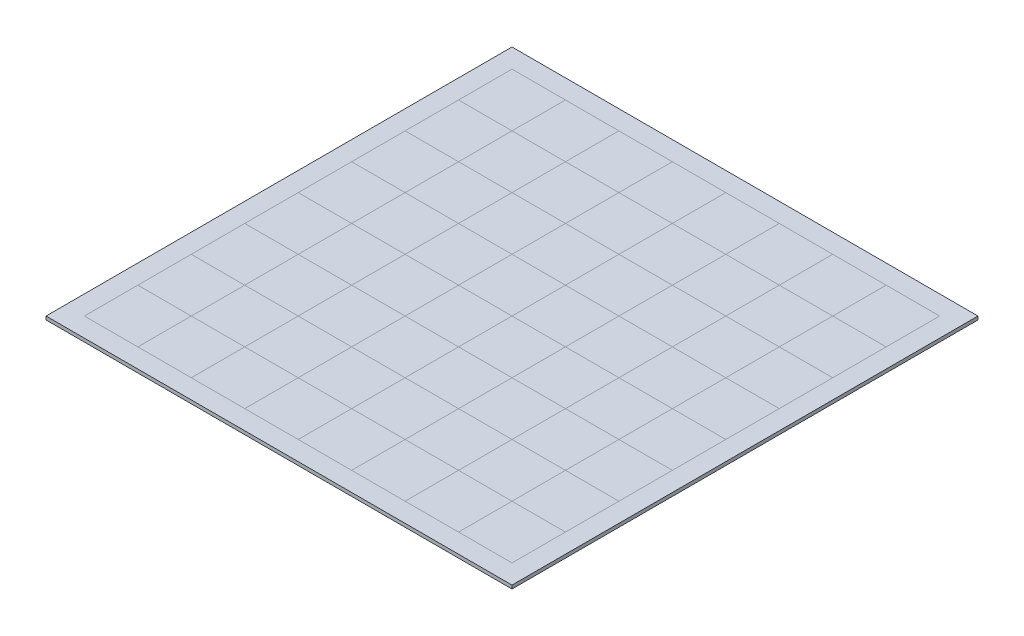
SolidWorks part; units mm, degrees
ref_plane "Front Plane" through (0, 0, 0) normal (0, 0, 1) x (1, 0, 0)
ref_plane "Top Plane" through (0, 0, 0) normal (0, 1, 0) x (1, 0, 0)
ref_plane "Right Plane" through (0, 0, 0) normal (1, 0, 0) x (0, 0, -1)
sketch "Sketch1" plane through (0, 0, 0) normal (0, 1, 0) x (1, 0, 0)
  line L0 (19.5, -19.5) -> (19.5, 19.5)
  line L1 (-19.5, -19.5) -> (19.5, -19.5)
  line L2 (-19.5, -19.5) -> (-19.5, 19.5)
  line L3 (-19.5, 19.5) -> (19.5, 19.5)
  line L4 (19.5, -19.5) -> (19.5, 19.5)
  line L5 (0, 19.5) -> (0, -19.5) construction
  line L6 (-19.5, 0) -> (19.5, 0) construction
  line L7 (19.5, 19.5) -> (58.5, 19.5)
  line L8 (19.5, -19.5) -> (58.5, -19.5)
  line L9 (58.5, -19.5) -> (58.5, 19.5)
  line L10 (58.5, -19.5) -> (58.5, 19.5)
  line L11 (58.5, 19.5) -> (97.5, 19.5)
  line L12 (58.5, -19.5) -> (97.5, -19.5)
  line L13 (97.5, -19.5) -> (97.5, 19.5)
  line L14 (97.5, -19.5) -> (97.5, 19.5)
  line L15 (97.5, 19.5) -> (136.5, 19.5)
  line L16 (97.5, -19.5) -> (136.5, -19.5)
  line L17 (136.5, -19.5) -> (136.5, 19.5)
  line L18 (136.5, -19.5) -> (136.5, 19.5)
  line L19 (136.5, 19.5) -> (175.5, 19.5)
  line L20 (136.5, -19.5) -> (175.5, -19.5)
  line L21 (175.5, -19.5) -> (175.5, 19.5)
  line L22 (175.5, -19.5) -> (175.5, 19.5)
  line L23 (175.5, 19.5) -> (214.5, 19.5)
  line L24 (175.5, -19.5) -> (214.5, -19.5)
  line L25 (214.5, -19.5) -> (214.5, 19.5)
  line L26 (214.5, -19.5) -> (214.5, 19.5)
  line L27 (214.5, 19.5) -> (253.5, 19.5)
  line L28 (214.5, -19.5) -> (253.5, -19.5)
  line L29 (253.5, -19.5) -> (253.5, 19.5)
  line L30 (253.5, -19.5) -> (253.5, 19.5)
  line L31 (253.5, 19.5) -> (292.5, 19.5)
  line L32 (253.5, -19.5) -> (292.5, -19.5)
  line L33 (292.5, -19.5) -> (292.5, 19.5)
  line L34 (19.5, 19.5) -> (19.5, 58.5)
  line L35 (19.5, 58.5) -> (58.5, 58.5)
  line L36 (19.5, 19.5) -> (58.5, 19.5)
  line L37 (58.5, 19.5) -> (58.5, 58.5)
  line L38 (58.5, 19.5) -> (58.5, 58.5)
  line L39 (58.5, 58.5) -> (97.5, 58.5)
  line L40 (58.5, 19.5) -> (97.5, 19.5)
  line L41 (97.5, 19.5) -> (97.5, 58.5)
  line L42 (97.5, 19.5) -> (97.5, 58.5)
  line L43 (97.5, 58.5) -> (136.5, 58.5)
  line L44 (97.5, 19.5) -> (136.5, 19.5)
  line L45 (136.5, 19.5) -> (136.5, 58.5)
  line L46 (136.5, 19.5) -> (136.5, 58.5)
  line L47 (136.5, 58.5) -> (175.5, 58.5)
  line L48 (136.5, 19.5) -> (175.5, 19.5)
  line L49 (175.5, 19.5) -> (175.5, 58.5)
  line L50 (175.5, 19.5) -> (175.5, 58.5)
  line L51 (175.5, 58.5) -> (214.5, 58.5)
  line L52 (175.5, 19.5) -> (214.5, 19.5)
  line L53 (214.5, 19.5) -> (214.5, 58.5)
  line L54 (214.5, 19.5) -> (214.5, 58.5)
  line L55 (214.5, 58.5) -> (253.5, 58.5)
  line L56 (214.5, 19.5) -> (253.5, 19.5)
  line L57 (253.5, 19.5) -> (253.5, 58.5)
  line L58 (253.5, 19.5) -> (253.5, 58.5)
  line L59 (253.5, 58.5) -> (292.5, 58.5)
  line L60 (253.5, 19.5) -> (292.5, 19.5)
  line L61 (292.5, 19.5) -> (292.5, 58.5)
  line L62 (19.5, 58.5) -> (19.5, 97.5)
  line L63 (19.5, 97.5) -> (58.5, 97.5)
  line L64 (19.5, 58.5) -> (58.5, 58.5)
  line L65 (58.5, 58.5) -> (58.5, 97.5)
  line L66 (58.5, 58.5) -> (58.5, 97.5)
  line L67 (58.5, 97.5) -> (97.5, 97.5)
  line L68 (58.5, 58.5) -> (97.5, 58.5)
  line L69 (97.5, 58.5) -> (97.5, 97.5)
  line L70 (97.5, 58.5) -> (97.5, 97.5)
  line L71 (97.5, 97.5) -> (136.5, 97.5)
  line L72 (97.5, 58.5) -> (136.5, 58.5)
  line L73 (136.5, 58.5) -> (136.5, 97.5)
  line L74 (136.5, 58.5) -> (136.5, 97.5)
  line L75 (136.5, 97.5) -> (175.5, 97.5)
  line L76 (136.5, 58.5) -> (175.5, 58.5)
  line L77 (175.5, 58.5) -> (175.5, 97.5)
  line L78 (175.5, 58.5) -> (175.5, 97.5)
  line L79 (175.5, 97.5) -> (214.5, 97.5)
  line L80 (175.5, 58.5) -> (214.5, 58.5)
  line L81 (214.5, 58.5) -> (214.5, 97.5)
  line L82 (214.5, 58.5) -> (214.5, 97.5)
  line L83 (214.5, 97.5) -> (253.5, 97.5)
  line L84 (214.5, 58.5) -> (253.5, 58.5)
  line L85 (253.5, 58.5) -> (253.5, 97.5)
  line L86 (253.5, 58.5) -> (253.5, 97.5)
  line L87 (253.5, 97.5) -> (292.5, 97.5)
  line L88 (253.5, 58.5) -> (292.5, 58.5)
  line L89 (292.5, 58.5) -> (292.5, 97.5)
  line L90 (19.5, 97.5) -> (19.5, 136.5)
  line L91 (19.5, 136.5) -> (58.5, 136.5)
  line L92 (19.5, 97.5) -> (58.5, 97.5)
  line L93 (58.5, 97.5) -> (58.5, 136.5)
  line L94 (58.5, 97.5) -> (58.5, 136.5)
  line L95 (58.5, 136.5) -> (97.5, 136.5)
  line L96 (58.5, 97.5) -> (97.5, 97.5)
  line L97 (97.5, 97.5) -> (97.5, 136.5)
  line L98 (97.5, 97.5) -> (97.5, 136.5)
  line L99 (97.5, 136.5) -> (136.5, 136.5)
  line L100 (97.5, 97.5) -> (136.5, 97.5)
  line L101 (136.5, 97.5) -> (136.5, 136.5)
  line L102 (136.5, 97.5) -> (136.5, 136.5)
  line L103 (136.5, 136.5) -> (175.5, 136.5)
  line L104 (136.5, 97.5) -> (175.5, 97.5)
  line L105 (175.5, 97.5) -> (175.5, 136.5)
  line L106 (175.5, 97.5) -> (175.5, 136.5)
  line L107 (175.5, 136.5) -> (214.5, 136.5)
  line L108 (175.5, 97.5) -> (214.5, 97.5)
  line L109 (214.5, 97.5) -> (214.5, 136.5)
  line L110 (214.5, 97.5) -> (214.5, 136.5)
  line L111 (214.5, 136.5) -> (253.5, 136.5)
  line L112 (214.5, 97.5) -> (253.5, 97.5)
  line L113 (253.5, 97.5) -> (253.5, 136.5)
  line L114 (253.5, 97.5) -> (253.5, 136.5)
  line L115 (253.5, 136.5) -> (292.5, 136.5)
  line L116 (253.5, 97.5) -> (292.5, 97.5)
  line L117 (292.5, 97.5) -> (292.5, 136.5)
  line L118 (19.5, 136.5) -> (19.5, 175.5)
  line L119 (19.5, 175.5) -> (58.5, 175.5)
  line L120 (19.5, 136.5) -> (58.5, 136.5)
  line L121 (58.5, 136.5) -> (58.5, 175.5)
  line L122 (58.5, 136.5) -> (58.5, 175.5)
  line L123 (58.5, 175.5) -> (97.5, 175.5)
  line L124 (58.5, 136.5) -> (97.5, 136.5)
  line L125 (97.5, 136.5) -> (97.5, 175.5)
  line L126 (97.5, 136.5) -> (97.5, 175.5)
  line L127 (97.5, 175.5) -> (136.5, 175.5)
  line L128 (97.5, 136.5) -> (136.5, 136.5)
  line L129 (136.5, 136.5) -> (136.5, 175.5)
  line L130 (136.5, 136.5) -> (136.5, 175.5)
  line L131 (136.5, 175.5) -> (175.5, 175.5)
  line L132 (136.5, 136.5) -> (175.5, 136.5)
  line L133 (175.5, 136.5) -> (175.5, 175.5)
  line L134 (175.5, 136.5) -> (175.5, 175.5)
  line L135 (175.5, 175.5) -> (214.5, 175.5)
  line L136 (175.5, 136.5) -> (214.5, 136.5)
  line L137 (214.5, 136.5) -> (214.5, 175.5)
  line L138 (214.5, 136.5) -> (214.5, 175.5)
  line L139 (214.5, 175.5) -> (253.5, 175.5)
  line L140 (214.5, 136.5) -> (253.5, 136.5)
  line L141 (253.5, 136.5) -> (253.5, 175.5)
  line L142 (253.5, 136.5) -> (253.5, 175.5)
  line L143 (253.5, 175.5) -> (292.5, 175.5)
  line L144 (253.5, 136.5) -> (292.5, 136.5)
  line L145 (292.5, 136.5) -> (292.5, 175.5)
  line L146 (19.5, 175.5) -> (19.5, 214.5)
  line L147 (19.5, 214.5) -> (58.5, 214.5)
  line L148 (19.5, 175.5) -> (58.5, 175.5)
  line L149 (58.5, 175.5) -> (58.5, 214.5)
  line L150 (58.5, 175.5) -> (58.5, 214.5)
  line L151 (58.5, 214.5) -> (97.5, 214.5)
  line L152 (58.5, 175.5) -> (97.5, 175.5)
  line L153 (97.5, 175.5) -> (97.5, 214.5)
  line L154 (97.5, 175.5) -> (97.5, 214.5)
  line L155 (97.5, 214.5) -> (136.5, 214.5)
  line L156 (97.5, 175.5) -> (136.5, 175.5)
  line L157 (136.5, 175.5) -> (136.5, 214.5)
  line L158 (136.5, 175.5) -> (136.5, 214.5)
  line L159 (136.5, 214.5) -> (175.5, 214.5)
  line L160 (136.5, 175.5) -> (175.5, 175.5)
  line L161 (175.5, 175.5) -> (175.5, 214.5)
  line L162 (175.5, 175.5) -> (175.5, 214.5)
  line L163 (175.5, 214.5) -> (214.5, 214.5)
  line L164 (175.5, 175.5) -> (214.5, 175.5)
  line L165 (214.5, 175.5) -> (214.5, 214.5)
  line L166 (214.5, 175.5) -> (214.5, 214.5)
  line L167 (214.5, 214.5) -> (253.5, 214.5)
  line L168 (214.5, 175.5) -> (253.5, 175.5)
  line L169 (253.5, 175.5) -> (253.5, 214.5)
  line L170 (253.5, 175.5) -> (253.5, 214.5)
  line L171 (253.5, 214.5) -> (292.5, 214.5)
  line L172 (253.5, 175.5) -> (292.5, 175.5)
  line L173 (292.5, 175.5) -> (292.5, 214.5)
  line L174 (19.5, 214.5) -> (19.5, 253.5)
  line L175 (19.5, 253.5) -> (58.5, 253.5)
  line L176 (19.5, 214.5) -> (58.5, 214.5)
  line L177 (58.5, 214.5) -> (58.5, 253.5)
  line L178 (58.5, 214.5) -> (58.5, 253.5)
  line L179 (58.5, 253.5) -> (97.5, 253.5)
  line L180 (58.5, 214.5) -> (97.5, 214.5)
  line L181 (97.5, 214.5) -> (97.5, 253.5)
  line L182 (97.5, 214.5) -> (97.5, 253.5)
  line L183 (97.5, 253.5) -> (136.5, 253.5)
  line L184 (97.5, 214.5) -> (136.5, 214.5)
  line L185 (136.5, 214.5) -> (136.5, 253.5)
  line L186 (136.5, 214.5) -> (136.5, 253.5)
  line L187 (136.5, 253.5) -> (175.5, 253.5)
  line L188 (136.5, 214.5) -> (175.5, 214.5)
  line L189 (175.5, 214.5) -> (175.5, 253.5)
  line L190 (175.5, 214.5) -> (175.5, 253.5)
  line L191 (175.5, 253.5) -> (214.5, 253.5)
  line L192 (175.5, 214.5) -> (214.5, 214.5)
  line L193 (214.5, 214.5) -> (214.5, 253.5)
  line L194 (214.5, 214.5) -> (214.5, 253.5)
  line L195 (214.5, 253.5) -> (253.5, 253.5)
  line L196 (214.5, 214.5) -> (253.5, 214.5)
  line L197 (253.5, 214.5) -> (253.5, 253.5)
  line L198 (253.5, 214.5) -> (253.5, 253.5)
  line L199 (253.5, 253.5) -> (292.5, 253.5)
  line L200 (253.5, 214.5) -> (292.5, 214.5)
  line L201 (292.5, 214.5) -> (292.5, 253.5)
  line L202 (19.5, 253.5) -> (19.5, 292.5)
  line L203 (19.5, 292.5) -> (58.5, 292.5)
  line L204 (19.5, 253.5) -> (58.5, 253.5)
  line L205 (58.5, 253.5) -> (58.5, 292.5)
  line L206 (58.5, 253.5) -> (58.5, 292.5)
  line L207 (58.5, 292.5) -> (97.5, 292.5)
  line L208 (58.5, 253.5) -> (97.5, 253.5)
  line L209 (97.5, 253.5) -> (97.5, 292.5)
  line L210 (97.5, 253.5) -> (97.5, 292.5)
  line L211 (97.5, 292.5) -> (136.5, 292.5)
  line L212 (97.5, 253.5) -> (136.5, 253.5)
  line L213 (136.5, 253.5) -> (136.5, 292.5)
  line L214 (136.5, 253.5) -> (136.5, 292.5)
  line L215 (136.5, 292.5) -> (175.5, 292.5)
  line L216 (136.5, 253.5) -> (175.5, 253.5)
  line L217 (175.5, 253.5) -> (175.5, 292.5)
  line L218 (175.5, 253.5) -> (175.5, 292.5)
  line L219 (175.5, 292.5) -> (214.5, 292.5)
  line L220 (175.5, 253.5) -> (214.5, 253.5)
  line L221 (214.5, 253.5) -> (214.5, 292.5)
  line L222 (214.5, 253.5) -> (214.5, 292.5)
  line L223 (214.5, 292.5) -> (253.5, 292.5)
  line L224 (214.5, 253.5) -> (253.5, 253.5)
  line L225 (253.5, 253.5) -> (253.5, 292.5)
  line L226 (253.5, 253.5) -> (253.5, 292.5)
  line L227 (253.5, 292.5) -> (292.5, 292.5)
  line L228 (253.5, 253.5) -> (292.5, 253.5)
  line L229 (292.5, 253.5) -> (292.5, 292.5)
  line L230 (-19.5, 19.5) -> (-19.5, 58.5)
  line L231 (-19.5, 58.5) -> (19.5, 58.5)
  line L232 (-19.5, 19.5) -> (19.5, 19.5)
  line L233 (19.5, 19.5) -> (19.5, 58.5)
  line L234 (-19.5, 58.5) -> (-19.5, 97.5)
  line L235 (-19.5, 97.5) -> (19.5, 97.5)
  line L236 (-19.5, 58.5) -> (19.5, 58.5)
  line L237 (19.5, 58.5) -> (19.5, 97.5)
  line L238 (-19.5, 97.5) -> (-19.5, 136.5)
  line L239 (-19.5, 136.5) -> (19.5, 136.5)
  line L240 (-19.5, 97.5) -> (19.5, 97.5)
  line L241 (19.5, 97.5) -> (19.5, 136.5)
  line L242 (-19.5, 136.5) -> (-19.5, 175.5)
  line L243 (-19.5, 175.5) -> (19.5, 175.5)
  line L244 (-19.5, 136.5) -> (19.5, 136.5)
  line L245 (19.5, 136.5) -> (19.5, 175.5)
  line L246 (-19.5, 175.5) -> (-19.5, 214.5)
  line L247 (-19.5, 214.5) -> (19.5, 214.5)
  line L248 (-19.5, 175.5) -> (19.5, 175.5)
  line L249 (19.5, 175.5) -> (19.5, 214.5)
  line L250 (-19.5, 214.5) -> (-19.5, 253.5)
  line L251 (-19.5, 253.5) -> (19.5, 253.5)
  line L252 (-19.5, 214.5) -> (19.5, 214.5)
  line L253 (19.5, 214.5) -> (19.5, 253.5)
  line L254 (-19.5, 253.5) -> (-19.5, 292.5)
  line L255 (-19.5, 292.5) -> (19.5, 292.5)
  line L256 (-19.5, 253.5) -> (19.5, 253.5)
  line L257 (19.5, 253.5) -> (19.5, 292.5)
  point P0 (0, 0)
  dimension "D1" = 39
  dimension "D2" = 39
  dimension "D3" = 8
extrude "Boss-Extrude1" add sketch "Sketch1" along normal blind 2.5 contours L3 L2 L1 L0 | L7 L37 L35 L34 | L12 L13 L11 L9 | L235 L234 L231 L62 | L39 L69 L67 L65 | L63 L93 L91 L90 | L243 L242 L239 L118 | L119 L149 L147 L146 | L251 L250 L247 L174 | L175 L205 L203 L202 | L151 L181 L179 L177 | L183 L213 L211 L209 | L127 L157 L155 L153 | L159 L189 L187 L185 | L191 L221 L219 L217 | L135 L165 L163 L161 | L167 L197 L195 L193 | L199 L229 L227 L225 | L143 L173 L171 L169 | L111 L141 L139 L137 | L79 L109 L107 L105 | L103 L133 L131 L129 | L95 L125 L123 L121 | L71 L101 L99 L97 | L47 L77 L75 L73 | L23 L53 L51 L49 | L15 L45 L43 L41 | L20 L21 L19 L17 | L28 L29 L27 L25 | L31 L61 L59 L57 | L55 L85 L83 L81 | L87 L117 L115 L113
sketch "Sketch4" plane through (0, 0, 0) normal (0, 1, 0) x (1, 0, 0)
  line L0 (58.5, 292.5) -> (19.5, 292.5)
  line L1 (19.5, 253.5) -> (-19.5, 253.5)
  line L2 (19.5, 253.5) -> (19.5, 292.5)
  line L3 (19.5, 292.5) -> (-19.5, 292.5)
  line L4 (-19.5, 253.5) -> (-19.5, 292.5)
  line L5 (19.5, 253.5) -> (19.5, 292.5)
  line L6 (58.5, 253.5) -> (58.5, 292.5)
  line L7 (58.5, 253.5) -> (19.5, 253.5)
  line L8 (97.5, 292.5) -> (58.5, 292.5)
  line L9 (58.5, 253.5) -> (58.5, 292.5)
  line L10 (97.5, 253.5) -> (97.5, 292.5)
  line L11 (97.5, 253.5) -> (58.5, 253.5)
  line L12 (136.5, 292.5) -> (97.5, 292.5)
  line L13 (97.5, 253.5) -> (97.5, 292.5)
  line L14 (136.5, 253.5) -> (136.5, 292.5)
  line L15 (136.5, 253.5) -> (97.5, 253.5)
  line L16 (175.5, 292.5) -> (136.5, 292.5)
  line L17 (136.5, 253.5) -> (136.5, 292.5)
  line L18 (175.5, 253.5) -> (175.5, 292.5)
  line L19 (175.5, 253.5) -> (136.5, 253.5)
  line L20 (214.5, 292.5) -> (175.5, 292.5)
  line L21 (175.5, 253.5) -> (175.5, 292.5)
  line L22 (214.5, 253.5) -> (214.5, 292.5)
  line L23 (214.5, 253.5) -> (175.5, 253.5)
  line L24 (253.5, 292.5) -> (214.5, 292.5)
  line L25 (214.5, 253.5) -> (214.5, 292.5)
  line L26 (253.5, 253.5) -> (253.5, 292.5)
  line L27 (253.5, 253.5) -> (214.5, 253.5)
  line L28 (292.5, 292.5) -> (253.5, 292.5)
  line L29 (253.5, 253.5) -> (253.5, 292.5)
  line L30 (292.5, 253.5) -> (292.5, 292.5)
  line L31 (292.5, 253.5) -> (253.5, 253.5)
  line L32 (58.5, 253.5) -> (19.5, 253.5)
  line L33 (19.5, 214.5) -> (19.5, 253.5)
  line L34 (58.5, 214.5) -> (58.5, 253.5)
  line L35 (58.5, 214.5) -> (19.5, 214.5)
  line L36 (97.5, 253.5) -> (58.5, 253.5)
  line L37 (58.5, 214.5) -> (58.5, 253.5)
  line L38 (97.5, 214.5) -> (97.5, 253.5)
  line L39 (97.5, 214.5) -> (58.5, 214.5)
  line L40 (136.5, 253.5) -> (97.5, 253.5)
  line L41 (97.5, 214.5) -> (97.5, 253.5)
  line L42 (136.5, 214.5) -> (136.5, 253.5)
  line L43 (136.5, 214.5) -> (97.5, 214.5)
  line L44 (175.5, 253.5) -> (136.5, 253.5)
  line L45 (136.5, 214.5) -> (136.5, 253.5)
  line L46 (175.5, 214.5) -> (175.5, 253.5)
  line L47 (175.5, 214.5) -> (136.5, 214.5)
  line L48 (214.5, 253.5) -> (175.5, 253.5)
  line L49 (175.5, 214.5) -> (175.5, 253.5)
  line L50 (214.5, 214.5) -> (214.5, 253.5)
  line L51 (214.5, 214.5) -> (175.5, 214.5)
  line L52 (253.5, 253.5) -> (214.5, 253.5)
  line L53 (214.5, 214.5) -> (214.5, 253.5)
  line L54 (253.5, 214.5) -> (253.5, 253.5)
  line L55 (253.5, 214.5) -> (214.5, 214.5)
  line L56 (292.5, 253.5) -> (253.5, 253.5)
  line L57 (253.5, 214.5) -> (253.5, 253.5)
  line L58 (292.5, 214.5) -> (292.5, 253.5)
  line L59 (292.5, 214.5) -> (253.5, 214.5)
  line L60 (58.5, 214.5) -> (19.5, 214.5)
  line L61 (19.5, 175.5) -> (19.5, 214.5)
  line L62 (58.5, 175.5) -> (58.5, 214.5)
  line L63 (58.5, 175.5) -> (19.5, 175.5)
  line L64 (97.5, 214.5) -> (58.5, 214.5)
  line L65 (58.5, 175.5) -> (58.5, 214.5)
  line L66 (97.5, 175.5) -> (97.5, 214.5)
  line L67 (97.5, 175.5) -> (58.5, 175.5)
  line L68 (136.5, 214.5) -> (97.5, 214.5)
  line L69 (97.5, 175.5) -> (97.5, 214.5)
  line L70 (136.5, 175.5) -> (136.5, 214.5)
  line L71 (136.5, 175.5) -> (97.5, 175.5)
  line L72 (175.5, 214.5) -> (136.5, 214.5)
  line L73 (136.5, 175.5) -> (136.5, 214.5)
  line L74 (175.5, 175.5) -> (175.5, 214.5)
  line L75 (175.5, 175.5) -> (136.5, 175.5)
  line L76 (214.5, 214.5) -> (175.5, 214.5)
  line L77 (175.5, 175.5) -> (175.5, 214.5)
  line L78 (214.5, 175.5) -> (214.5, 214.5)
  line L79 (214.5, 175.5) -> (175.5, 175.5)
  line L80 (253.5, 214.5) -> (214.5, 214.5)
  line L81 (214.5, 175.5) -> (214.5, 214.5)
  line L82 (253.5, 175.5) -> (253.5, 214.5)
  line L83 (253.5, 175.5) -> (214.5, 175.5)
  line L84 (292.5, 214.5) -> (253.5, 214.5)
  line L85 (253.5, 175.5) -> (253.5, 214.5)
  line L86 (292.5, 175.5) -> (292.5, 214.5)
  line L87 (292.5, 175.5) -> (253.5, 175.5)
  line L88 (58.5, 175.5) -> (19.5, 175.5)
  line L89 (19.5, 136.5) -> (19.5, 175.5)
  line L90 (58.5, 136.5) -> (58.5, 175.5)
  line L91 (58.5, 136.5) -> (19.5, 136.5)
  line L92 (97.5, 175.5) -> (58.5, 175.5)
  line L93 (58.5, 136.5) -> (58.5, 175.5)
  line L94 (97.5, 136.5) -> (97.5, 175.5)
  line L95 (97.5, 136.5) -> (58.5, 136.5)
  line L96 (136.5, 175.5) -> (97.5, 175.5)
  line L97 (97.5, 136.5) -> (97.5, 175.5)
  line L98 (136.5, 136.5) -> (136.5, 175.5)
  line L99 (136.5, 136.5) -> (97.5, 136.5)
  line L100 (175.5, 175.5) -> (136.5, 175.5)
  line L101 (136.5, 136.5) -> (136.5, 175.5)
  line L102 (175.5, 136.5) -> (175.5, 175.5)
  line L103 (175.5, 136.5) -> (136.5, 136.5)
  line L104 (214.5, 175.5) -> (175.5, 175.5)
  line L105 (175.5, 136.5) -> (175.5, 175.5)
  line L106 (214.5, 136.5) -> (214.5, 175.5)
  line L107 (214.5, 136.5) -> (175.5, 136.5)
  line L108 (253.5, 175.5) -> (214.5, 175.5)
  line L109 (214.5, 136.5) -> (214.5, 175.5)
  line L110 (253.5, 136.5) -> (253.5, 175.5)
  line L111 (253.5, 136.5) -> (214.5, 136.5)
  line L112 (292.5, 175.5) -> (253.5, 175.5)
  line L113 (253.5, 136.5) -> (253.5, 175.5)
  line L114 (292.5, 136.5) -> (292.5, 175.5)
  line L115 (292.5, 136.5) -> (253.5, 136.5)
  line L116 (58.5, 136.5) -> (19.5, 136.5)
  line L117 (19.5, 97.5) -> (19.5, 136.5)
  line L118 (58.5, 97.5) -> (58.5, 136.5)
  line L119 (58.5, 97.5) -> (19.5, 97.5)
  line L120 (97.5, 136.5) -> (58.5, 136.5)
  line L121 (58.5, 97.5) -> (58.5, 136.5)
  line L122 (97.5, 97.5) -> (97.5, 136.5)
  line L123 (97.5, 97.5) -> (58.5, 97.5)
  line L124 (136.5, 136.5) -> (97.5, 136.5)
  line L125 (97.5, 97.5) -> (97.5, 136.5)
  line L126 (136.5, 97.5) -> (136.5, 136.5)
  line L127 (136.5, 97.5) -> (97.5, 97.5)
  line L128 (175.5, 136.5) -> (136.5, 136.5)
  line L129 (136.5, 97.5) -> (136.5, 136.5)
  line L130 (175.5, 97.5) -> (175.5, 136.5)
  line L131 (175.5, 97.5) -> (136.5, 97.5)
  line L132 (214.5, 136.5) -> (175.5, 136.5)
  line L133 (175.5, 97.5) -> (175.5, 136.5)
  line L134 (214.5, 97.5) -> (214.5, 136.5)
  line L135 (214.5, 97.5) -> (175.5, 97.5)
  line L136 (253.5, 136.5) -> (214.5, 136.5)
  line L137 (214.5, 97.5) -> (214.5, 136.5)
  line L138 (253.5, 97.5) -> (253.5, 136.5)
  line L139 (253.5, 97.5) -> (214.5, 97.5)
  line L140 (292.5, 136.5) -> (253.5, 136.5)
  line L141 (253.5, 97.5) -> (253.5, 136.5)
  line L142 (292.5, 97.5) -> (292.5, 136.5)
  line L143 (292.5, 97.5) -> (253.5, 97.5)
  line L144 (58.5, 97.5) -> (19.5, 97.5)
  line L145 (19.5, 58.5) -> (19.5, 97.5)
  line L146 (58.5, 58.5) -> (58.5, 97.5)
  line L147 (58.5, 58.5) -> (19.5, 58.5)
  line L148 (97.5, 97.5) -> (58.5, 97.5)
  line L149 (58.5, 58.5) -> (58.5, 97.5)
  line L150 (97.5, 58.5) -> (97.5, 97.5)
  line L151 (97.5, 58.5) -> (58.5, 58.5)
  line L152 (136.5, 97.5) -> (97.5, 97.5)
  line L153 (97.5, 58.5) -> (97.5, 97.5)
  line L154 (136.5, 58.5) -> (136.5, 97.5)
  line L155 (136.5, 58.5) -> (97.5, 58.5)
  line L156 (175.5, 97.5) -> (136.5, 97.5)
  line L157 (136.5, 58.5) -> (136.5, 97.5)
  line L158 (175.5, 58.5) -> (175.5, 97.5)
  line L159 (175.5, 58.5) -> (136.5, 58.5)
  line L160 (214.5, 97.5) -> (175.5, 97.5)
  line L161 (175.5, 58.5) -> (175.5, 97.5)
  line L162 (214.5, 58.5) -> (214.5, 97.5)
  line L163 (214.5, 58.5) -> (175.5, 58.5)
  line L164 (253.5, 97.5) -> (214.5, 97.5)
  line L165 (214.5, 58.5) -> (214.5, 97.5)
  line L166 (253.5, 58.5) -> (253.5, 97.5)
  line L167 (253.5, 58.5) -> (214.5, 58.5)
  line L168 (292.5, 97.5) -> (253.5, 97.5)
  line L169 (253.5, 58.5) -> (253.5, 97.5)
  line L170 (292.5, 58.5) -> (292.5, 97.5)
  line L171 (292.5, 58.5) -> (253.5, 58.5)
  line L172 (58.5, 58.5) -> (19.5, 58.5)
  line L173 (19.5, 19.5) -> (19.5, 58.5)
  line L174 (58.5, 19.5) -> (58.5, 58.5)
  line L175 (58.5, 19.5) -> (19.5, 19.5)
  line L176 (97.5, 58.5) -> (58.5, 58.5)
  line L177 (58.5, 19.5) -> (58.5, 58.5)
  line L178 (97.5, 19.5) -> (97.5, 58.5)
  line L179 (97.5, 19.5) -> (58.5, 19.5)
  line L180 (136.5, 58.5) -> (97.5, 58.5)
  line L181 (97.5, 19.5) -> (97.5, 58.5)
  line L182 (136.5, 19.5) -> (136.5, 58.5)
  line L183 (136.5, 19.5) -> (97.5, 19.5)
  line L184 (175.5, 58.5) -> (136.5, 58.5)
  line L185 (136.5, 19.5) -> (136.5, 58.5)
  line L186 (175.5, 19.5) -> (175.5, 58.5)
  line L187 (175.5, 19.5) -> (136.5, 19.5)
  line L188 (214.5, 58.5) -> (175.5, 58.5)
  line L189 (175.5, 19.5) -> (175.5, 58.5)
  line L190 (214.5, 19.5) -> (214.5, 58.5)
  line L191 (214.5, 19.5) -> (175.5, 19.5)
  line L192 (253.5, 58.5) -> (214.5, 58.5)
  line L193 (214.5, 19.5) -> (214.5, 58.5)
  line L194 (253.5, 19.5) -> (253.5, 58.5)
  line L195 (253.5, 19.5) -> (214.5, 19.5)
  line L196 (292.5, 58.5) -> (253.5, 58.5)
  line L197 (253.5, 19.5) -> (253.5, 58.5)
  line L198 (292.5, 19.5) -> (292.5, 58.5)
  line L199 (292.5, 19.5) -> (253.5, 19.5)
  line L200 (58.5, 19.5) -> (19.5, 19.5)
  line L201 (19.5, -19.5) -> (19.5, 19.5)
  line L202 (58.5, -19.5) -> (58.5, 19.5)
  line L203 (58.5, -19.5) -> (19.5, -19.5)
  line L204 (97.5, 19.5) -> (58.5, 19.5)
  line L205 (58.5, -19.5) -> (58.5, 19.5)
  line L206 (97.5, -19.5) -> (97.5, 19.5)
  line L207 (97.5, -19.5) -> (58.5, -19.5)
  line L208 (136.5, 19.5) -> (97.5, 19.5)
  line L209 (97.5, -19.5) -> (97.5, 19.5)
  line L210 (136.5, -19.5) -> (136.5, 19.5)
  line L211 (136.5, -19.5) -> (97.5, -19.5)
  line L212 (175.5, 19.5) -> (136.5, 19.5)
  line L213 (136.5, -19.5) -> (136.5, 19.5)
  line L214 (175.5, -19.5) -> (175.5, 19.5)
  line L215 (175.5, -19.5) -> (136.5, -19.5)
  line L216 (214.5, 19.5) -> (175.5, 19.5)
  line L217 (175.5, -19.5) -> (175.5, 19.5)
  line L218 (214.5, -19.5) -> (214.5, 19.5)
  line L219 (214.5, -19.5) -> (175.5, -19.5)
  line L220 (253.5, 19.5) -> (214.5, 19.5)
  line L221 (214.5, -19.5) -> (214.5, 19.5)
  line L222 (253.5, -19.5) -> (253.5, 19.5)
  line L223 (253.5, -19.5) -> (214.5, -19.5)
  line L224 (292.5, 19.5) -> (253.5, 19.5)
  line L225 (253.5, -19.5) -> (253.5, 19.5)
  line L226 (292.5, -19.5) -> (292.5, 19.5)
  line L227 (292.5, -19.5) -> (253.5, -19.5)
  line L228 (19.5, 253.5) -> (-19.5, 253.5)
  line L229 (-19.5, 214.5) -> (-19.5, 253.5)
  line L230 (19.5, 214.5) -> (19.5, 253.5)
  line L231 (19.5, 214.5) -> (-19.5, 214.5)
  line L232 (19.5, 214.5) -> (-19.5, 214.5)
  line L233 (-19.5, 175.5) -> (-19.5, 214.5)
  line L234 (19.5, 175.5) -> (19.5, 214.5)
  line L235 (19.5, 175.5) -> (-19.5, 175.5)
  line L236 (19.5, 175.5) -> (-19.5, 175.5)
  line L237 (-19.5, 136.5) -> (-19.5, 175.5)
  line L238 (19.5, 136.5) -> (19.5, 175.5)
  line L239 (19.5, 136.5) -> (-19.5, 136.5)
  line L240 (19.5, 136.5) -> (-19.5, 136.5)
  line L241 (-19.5, 97.5) -> (-19.5, 136.5)
  line L242 (19.5, 97.5) -> (19.5, 136.5)
  line L243 (19.5, 97.5) -> (-19.5, 97.5)
  line L244 (19.5, 97.5) -> (-19.5, 97.5)
  line L245 (-19.5, 58.5) -> (-19.5, 97.5)
  line L246 (19.5, 58.5) -> (19.5, 97.5)
  line L247 (19.5, 58.5) -> (-19.5, 58.5)
  line L248 (19.5, 58.5) -> (-19.5, 58.5)
  line L249 (-19.5, 19.5) -> (-19.5, 58.5)
  line L250 (19.5, 19.5) -> (19.5, 58.5)
  line L251 (19.5, 19.5) -> (-19.5, 19.5)
  line L252 (19.5, 19.5) -> (-19.5, 19.5)
  line L253 (-19.5, -19.5) -> (-19.5, 19.5)
  line L254 (19.5, -19.5) -> (19.5, 19.5)
  line L255 (19.5, -19.5) -> (-19.5, -19.5)
  dimension "D1" = 39
  dimension "D2" = 39
extrude "Boss-Extrude2" add sketch "Sketch4" along normal blind 2.5 separate body contours L4 L1 L2 L3 | L35 L34 L7 L33 | L11 L10 L8 L6 | L235 L61 L231 L233 | L67 L66 L39 L62 | L91 L90 L63 L89 | L243 L117 L239 L241 | L123 L122 L95 L118 | L147 L146 L119 L145 | L251 L173 L247 L249 | L203 L202 L175 L201 | L179 L178 L151 L174 | L211 L210 L183 L206 | L155 L154 L127 L150 | L99 L98 L71 L94 | L43 L42 L15 L38 | L19 L18 L16 L14 | L51 L50 L23 L46 | L75 L74 L47 L70 | L131 L130 L103 L126 | L107 L106 L79 L102 | L83 L82 L55 L78 | L59 L58 L31 L54 | L27 L26 L24 L22 | L115 L114 L87 L110 | L139 L138 L111 L134 | L163 L162 L135 L158 | L171 L170 L143 L166 | L195 L194 L167 L190 | L187 L186 L159 L182 | L219 L218 L191 L214 | L227 L226 L199 L222
sketch "Sketch5" plane through (0, 0, 0) normal (0, 1, 0) x (1, 0, 0)
  line L0 (-33.5, 306.5) -> (-19.5, 292.5) construction
  line L1 (-33.5, 306.5) -> (306.5, 306.5)
  line L2 (-33.5, 306.5) -> (-33.5, -33.5)
  line L3 (-33.5, -33.5) -> (306.5, -33.5)
  line L4 (306.5, 306.5) -> (306.5, -33.5)
  line L5 (292.5, -19.5) -> (306.5, -33.5) construction
  line L7 (-19.5, 292.5) -> (292.5, 292.5)
  line L8 (-19.5, 292.5) -> (-19.5, -19.5)
  line L9 (-19.5, -19.5) -> (292.5, -19.5)
  line L10 (292.5, 292.5) -> (292.5, -19.5)
  dimension "D1" = 340
  dimension "D2" = 340
extrude "Boss-Extrude3" add sketch "Sketch5" along normal blind 2.5 separate body
